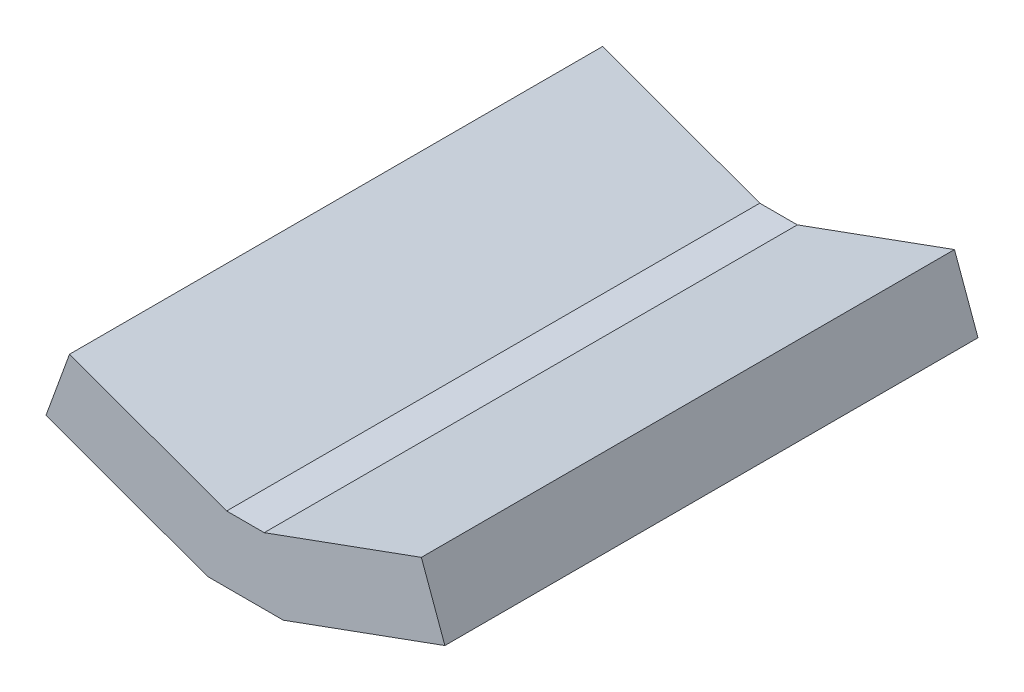
SolidWorks part; units mm, degrees
ref_plane "Front" through (0, 0, 0) normal (0, 0, 1) x (1, 0, 0)
ref_plane "Top" through (0, 0, 0) normal (0, 1, 0) x (1, 0, 0)
ref_plane "Right" through (0, 0, 0) normal (1, 0, 0) x (0, 0, -1)
sketch "Top Layout" plane through (0, 0, 0) normal (0, 1, 0) x (1, 0, 0)
  line L0 (53, 68) -> (61, 68) construction
  line L1 (61, 118) -> (61, 18) construction
  line L2 (64, 0) -> (72, 0) construction
  line L3 (72, 50) -> (72, -50) construction
  line L4 (37, -68) -> (45, -68) construction
  line L5 (45, -18) -> (45, -118) construction
  line L6 (0, 30.1091) -> (0, 0) construction
  line L11 (49.5, 10) -> (49.5, 43.5) construction
  line B0 (50, 45.5) -> (27, 45.5) construction
  line B1 (50, 77.5) -> (50, 43.5) construction
  line B2 (50, 77.5) -> (27, 77.5) construction
  line B3 (27, 77.5) -> (27, 43.5) construction
  line B4 (50, 43.5) -> (27, 43.5) construction
  line B5 (50, 75.5) -> (27, 75.5) construction
  line B6 (24, 68) -> (53, 68) construction
  line B7 (11, -45.5) -> (34, -45.5) construction
  line B8 (11, -77.5) -> (11, -43.5) construction
  line B9 (11, -77.5) -> (34, -77.5) construction
  line B10 (34, -77.5) -> (34, -43.5) construction
  line B11 (11, -43.5) -> (34, -43.5) construction
  line B12 (11, -75.5) -> (34, -75.5) construction
  line B13 (37, -68) -> (8, -68) construction
  line B14 (-14.5, 30.1091) -> (14.5, 30.1091) construction
  line B15 (-11.5, 20.1091) -> (-11.5, 40.1091) construction
  line B16 (-11.5, 20.1091) -> (11.5, 20.1091) construction
  line B17 (11.5, 20.1091) -> (11.5, 40.1091) construction
  line B18 (-11.5, 40.1091) -> (11.5, 40.1091) construction
  line B19 (35, 0) -> (64, 0) construction
  line B20 (38, -10) -> (38, 10) construction
  line B21 (38, -10) -> (61, -10) construction
  line B22 (61, -10) -> (61, 10) construction
  line B23 (38, 10) -> (61, 10) construction
  dimension "D1" = 8
  dimension "D2" = 100
  dimension "D3" = 3
  dimension "D4" = 8
  dimension "D5" = 72
  dimension "D6" = 45
  dimension "D7" = 8
sketch_block_instance "DYNAMIXEL 330 Side-3"
sketch_block "DYNAMIXEL 330 Side" parameters "D1"=30, "D2"=34, "D3"=23, "D4"=2, "D5"=33.2021, "D6"=6.9234, "D7"=26.2787
sketch_block_instance "DYNAMIXEL 330 Side-4"
sketch_block_instance "Block1-1"
sketch_block "Block1" parameters "D1"=23, "D2"=20, "D3"=3, "D4"=3
sketch_block_instance "Block1-2"
sketch "Sketch7" plane through (0, 0, 0) normal (0, 0, 1) x (1, 0, 0)
  line L0 (-11, 0) -> (11, 0)
  line L1 (11, 0) -> (57.9846, 17.101)
  line L2 (57.9846, 17.101) -> (51.1442, 35.8949)
  line L3 (51.1442, 35.8949) -> (5.4622, 19.268)
  line L4 (5.4622, 19.268) -> (-5.4622, 19.268)
  line L5 (11, 0) -> (61, 0) construction
  line L6 (35, 0) -> (64, 0) construction
  line L7 (0, -50) -> (0, 50) construction
  line L8 (-11, 0) -> (-61, 0) construction
  line L9 (-51.1442, 35.8949) -> (-5.4622, 19.268)
  line L10 (-57.9846, 17.101) -> (-51.1442, 35.8949)
  line L11 (-11, 0) -> (-57.9846, 17.101)
  point P5 (0, 0)
  point P8 (0, 17.1088)
  point P12 (-15.0079, 17.7452)
  point P13 (-4.8262, 15.7452)
  point P14 (50.3801, 36.7316)
  point P16 (18.5306, 27.4418)
  point P17 (-3.1975, 24.8254)
  point P22 (0, 0)
  point P28 (0, 19.268)
  point P30 (0, 0)
  dimension "D1" = 20
  dimension "D2" = 20
extrude "Boss-Extrude2" add sketch "Sketch7" along normal up to vertex (77.5 mm away) and the other way up to vertex (77.5 mm away)
sketch "Sketch8" plane through (1.2868, -3.5353, -16.2378) normal (0.342, -0.9397, 0) x (0.883, 0.3214, -0.342)
  line L0 (52.5953, 69.1119) -> (60.5953, 69.1119) construction
  line L1 (60.5953, 119.1119) -> (60.5953, 19.1119) construction
  line L2 (63.5953, 1.1119) -> (71.5953, 1.1119) construction
  line L3 (71.5953, 51.1119) -> (71.5953, -48.8881) construction
  line L4 (36.5953, -66.8881) -> (44.5953, -66.8881) construction
  line L5 (44.5953, -16.8881) -> (44.5953, -116.8881) construction
  line L6 (-0.4047, 30.1091) -> (-0.4047, 1.1119) construction
  line L11 (49.0953, 11.1119) -> (49.0953, 44.6119) construction
  line L12 (4.7443, -13.0348) -> (-5.5536, 15.2585) construction
  point P14 (-0.4047, 1.1119)
  line B0 (49.5953, 46.6119) -> (26.5953, 46.6119) construction
  line B1 (49.5953, 78.6119) -> (49.5953, 44.6119) construction
  line B2 (49.5953, 78.6119) -> (26.5953, 78.6119) construction
  line B3 (26.5953, 78.6119) -> (26.5953, 44.6119) construction
  line B4 (49.5953, 44.6119) -> (26.5953, 44.6119) construction
  line B5 (49.5953, 76.6119) -> (26.5953, 76.6119) construction
  line B6 (23.5953, 69.1119) -> (52.5953, 69.1119) construction
  line B7 (10.5953, -44.3881) -> (33.5953, -44.3881) construction
  line B8 (10.5953, -76.3881) -> (10.5953, -42.3881) construction
  line B9 (10.5953, -76.3881) -> (33.5953, -76.3881) construction
  line B10 (33.5953, -76.3881) -> (33.5953, -42.3881) construction
  line B11 (10.5953, -42.3881) -> (33.5953, -42.3881) construction
  line B12 (10.5953, -74.3881) -> (33.5953, -74.3881) construction
  line B13 (36.5953, -66.8881) -> (7.5953, -66.8881) construction
  line B14 (-14.9047, 30.1091) -> (14.0953, 30.1091) construction
  line B15 (-11.9047, 20.1091) -> (-11.9047, 40.1091) construction
  line B16 (-11.9047, 20.1091) -> (11.0953, 20.1091) construction
  line B17 (11.0953, 20.1091) -> (11.0953, 40.1091) construction
  line B18 (-11.9047, 40.1091) -> (11.0953, 40.1091) construction
  line B19 (34.5953, 1.1119) -> (63.5953, 1.1119) construction
  line B20 (37.5953, -8.8881) -> (37.5953, 11.1119) construction
  line B21 (37.5953, -8.8881) -> (60.5953, -8.8881) construction
  line B22 (60.5953, -8.8881) -> (60.5953, 11.1119) construction
  line B23 (37.5953, 11.1119) -> (60.5953, 11.1119) construction
  dimension "D1" = 8
  dimension "D2" = 100
  dimension "D3" = 3
  dimension "D4" = 8
  dimension "D5" = 72
  dimension "D6" = 45
  dimension "D7" = 8
sketch_block_instance "DYNAMIXEL 330 Side-8"
sketch_block_instance "DYNAMIXEL 330 Side-9"
sketch_block_instance "Block1-3"
sketch_block_instance "Block1-4"
